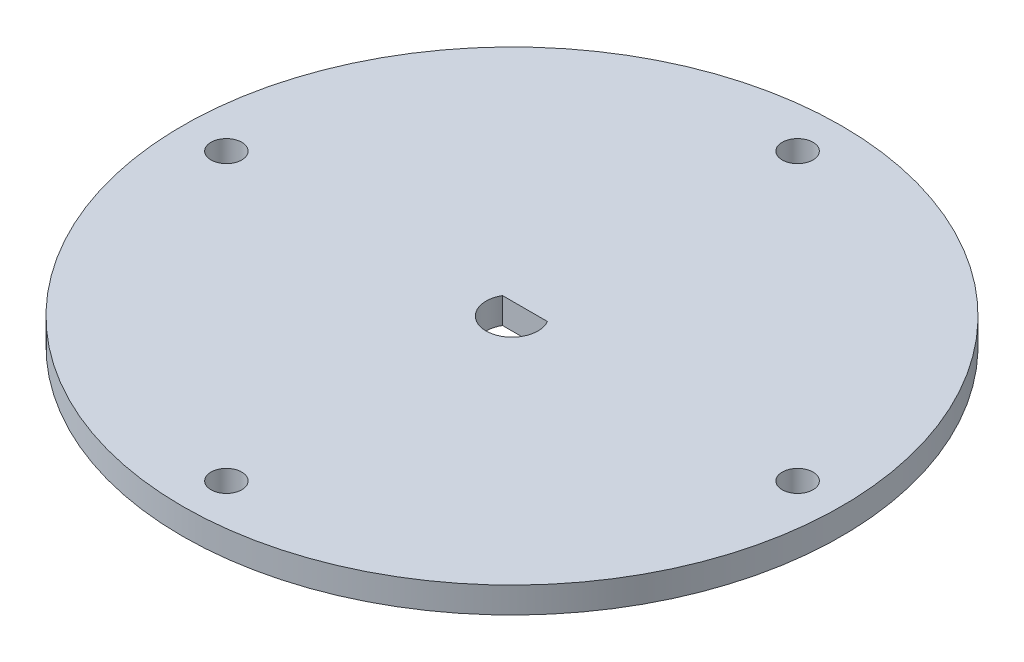
SolidWorks part; units mm, degrees
ref_plane "Front Plane" through (0, 0, 0) normal (0, 0, 1) x (1, 0, 0)
ref_plane "Top Plane" through (0, 0, 0) normal (0, 1, 0) x (1, 0, 0)
ref_plane "Right Plane" through (0, 0, 0) normal (1, 0, 0) x (0, 0, -1)
sketch "Sketch1" plane through (0, 0, 0) normal (0, 1, 0) x (1, 0, 0)
  circle A0 centre (0, 0) radius 38.1
  dimension "D1" = 76.2
extrude "Boss-Extrude1" add sketch "Sketch1" along normal blind 3
sketch "Sketch3" plane through (0, 3, 0) normal (0, 1, 0) x (1, 0, 0)
  line L0 (0, 0) -> (33.02, 0) construction
  circle A0 centre (33.02, 0) radius 1.778
  dimension "D1" = 3.556
  dimension "D2" = 33.02
extrude "Cut-Extrude1" cut sketch "Sketch3" against normal through all
pattern_circular "CirPattern1" count 4 over 360 about axis through (0, 0, 0) along (0, 1, 0) of "Cut-Extrude1"
sketch "Sketch4" plane through (0, 3, 0) normal (0, 1, 0) x (1, 0, 0)
  line L0 (-2.5981, 1.5) -> (2.5981, 1.5)
  arc A0 (-2.5981, 1.5) -> (2.5981, 1.5) centre (0, 0) ccw
  dimension "D1" = 6
  dimension "D2" = 1.5
extrude "Cut-Extrude2" cut sketch "Sketch4" against normal through all
